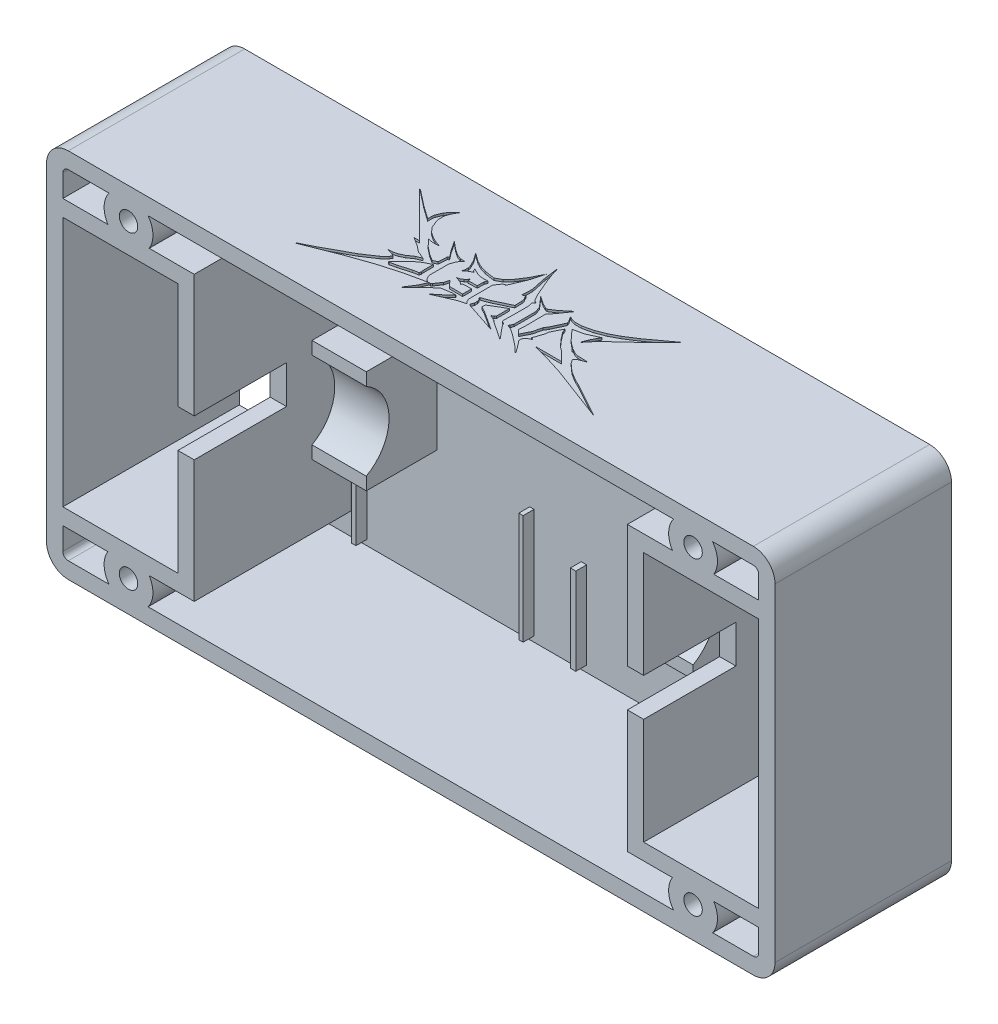
SolidWorks part; units mm, degrees
material "Overture Super PLA Plus"
ref_plane "Front Plane" through (0, 0, 0) normal (0, 0, 1) x (1, 0, 0)
ref_plane "Top Plane" through (0, 0, 0) normal (0, 1, 0) x (1, 0, 0)
ref_plane "Right Plane" through (0, 0, 0) normal (1, 0, 0) x (0, 0, -1)
sketch "Base_Footprint" plane through (0, 0, 0) normal (0, 0, 1) x (1, 0, 0)
  line L1 (-67.1, -34.2) -> (67.1, -34.2)
  line L2 (-67.1, -34.2) -> (-67.1, 34.2)
  line L3 (-67.1, 34.2) -> (67.1, 34.2)
  line L4 (67.1, -34.2) -> (67.1, 34.2)
  dimension "R1_Width" = 134.2
  dimension "R1_Length" = 68.4
  dimension "R1_X" = 67.1
  dimension "R1_Y" = 34.2
extrude "Unbroken_Floor" add sketch "Base_Footprint" along normal blind 2.6
sketch "Shell_Profile" plane through (0, 0, 0) normal (0, 0, 1) x (1, 0, 0)
  line L1 (-67.1, -34.2) -> (67.1, -34.2)
  line L2 (-67.1, -34.2) -> (-67.1, 34.2)
  line L3 (-67.1, 34.2) -> (67.1, 34.2)
  line L4 (67.1, -34.2) -> (67.1, 34.2)
  line L6 (-64.1, -31.2) -> (64.1, -31.2)
  line L7 (-64.1, -31.2) -> (-64.1, 31.2)
  line L8 (-64.1, 31.2) -> (64.1, 31.2)
  line L9 (64.1, -31.2) -> (64.1, 31.2)
  dimension "R1_Width" = 134.2
  dimension "R1_Length" = 68.4
  dimension "R1_X" = 67.1
  dimension "R1_Y" = 34.2
  dimension "R2_Width" = 128.2
  dimension "R2_Length" = 62.4
  dimension "R2_X" = 64.1
  dimension "R2_Y" = 31.2
extrude "Three_mm_Perimeter" add sketch "Shell_Profile" along normal blind 32.5
sketch "Wheel_Well_Profile" plane through (0, 0, 0) normal (0, 0, 1) x (1, 0, 0)
  line L1 (42.9, -23.1) -> (64.1, -23.1)
  line L2 (42.9, -23.1) -> (42.9, 23.1)
  line L3 (42.9, 23.1) -> (64.1, 23.1)
  line L4 (64.1, -23.1) -> (64.1, 23.1)
  line L6 (-64.1, -23.1) -> (-42.9, -23.1)
  line L7 (-64.1, -23.1) -> (-64.1, 23.1)
  line L8 (-64.1, 23.1) -> (-42.9, 23.1)
  line L9 (-42.9, -23.1) -> (-42.9, 23.1)
  dimension "R2_X" = 64.1
  dimension "R1_Width" = 21.2
  dimension "R1_Length" = 46.2
  dimension "R1_X" = 42.9
  dimension "R1_Y" = 23.1
  dimension "R2_Width" = 21.2
  dimension "R2_Length" = 46.2
  dimension "R2_Y" = 23.1
extrude "Open_Wheel_Wells" cut sketch "Wheel_Well_Profile" against normal blind 38 from offset 36
sketch "Wheel_Guard_Profile" plane through (0, 0, 0) normal (0, 0, 1) x (1, 0, 0)
  line L1 (39.9, -23.1) -> (42.9, -23.1)
  line L2 (39.9, -23.1) -> (39.9, 23.1)
  line L3 (39.9, 23.1) -> (42.9, 23.1)
  line L4 (42.9, -23.1) -> (42.9, 23.1)
  line L6 (-42.9, -23.1) -> (-39.9, -23.1)
  line L7 (-42.9, -23.1) -> (-42.9, 23.1)
  line L8 (-42.9, 23.1) -> (-39.9, 23.1)
  line L9 (-39.9, -23.1) -> (-39.9, 23.1)
  dimension "R1_Width" = 3
  dimension "R1_Length" = 46.2
  dimension "R1_X" = 39.9
  dimension "R1_Y" = 23.1
  dimension "R2_Width" = 3
  dimension "R2_Length" = 46.2
  dimension "R2_X" = 42.9
  dimension "R2_Y" = 23.1
extrude "Inner_Wheel_Guards" add sketch "Wheel_Guard_Profile" along normal blind 32.5
sketch "Wheel_Return_Profile" plane through (0, 0, 0) normal (0, 0, 1) x (1, 0, 0)
  line L1 (-64.1, -26.1) -> (-39.9, -26.1)
  line L2 (-64.1, -26.1) -> (-64.1, -23.1)
  line L3 (-64.1, -23.1) -> (-39.9, -23.1)
  line L4 (-39.9, -26.1) -> (-39.9, -23.1)
  line L6 (-64.1, 23.1) -> (-39.9, 23.1)
  line L7 (-64.1, 23.1) -> (-64.1, 26.1)
  line L8 (-64.1, 26.1) -> (-39.9, 26.1)
  line L9 (-39.9, 23.1) -> (-39.9, 26.1)
  line L11 (39.9, -26.1) -> (64.1, -26.1)
  line L12 (39.9, -26.1) -> (39.9, -23.1)
  line L13 (39.9, -23.1) -> (64.1, -23.1)
  line L14 (64.1, -26.1) -> (64.1, -23.1)
  line L16 (39.9, 23.1) -> (64.1, 23.1)
  line L17 (39.9, 23.1) -> (39.9, 26.1)
  line L18 (39.9, 26.1) -> (64.1, 26.1)
  line L19 (64.1, 23.1) -> (64.1, 26.1)
  dimension "R1_Width" = 24.2
  dimension "R1_Length" = 3
  dimension "R1_X" = 64.1
  dimension "R1_Y" = 26.1
  dimension "R2_Width" = 24.2
  dimension "R2_Length" = 3
  dimension "R2_X" = 64.1
  dimension "R2_Y" = 23.1
  dimension "R3_Width" = 24.2
  dimension "R3_Length" = 3
  dimension "R3_X" = 39.9
  dimension "R3_Y" = 26.1
  dimension "R4_Width" = 24.2
  dimension "R4_Length" = 3
  dimension "R4_X" = 39.9
  dimension "R4_Y" = 23.1
extrude "Wheel_Return_Ribs" add sketch "Wheel_Return_Profile" along normal blind 32.5
sketch "Shaft_Drop_In_Profile" plane through (0, 0, 0) normal (0, 0, 1) x (1, 0, 0)
  line L1 (-43.2, -3.5) -> (-39.5, -3.5)
  line L2 (-43.2, -3.5) -> (-43.2, 3.5)
  line L3 (-43.2, 3.5) -> (-39.5, 3.5)
  line L4 (-39.5, -3.5) -> (-39.5, 3.5)
  line L6 (39.5, -3.5) -> (43.2, -3.5)
  line L7 (39.5, -3.5) -> (39.5, 3.5)
  line L8 (39.5, 3.5) -> (43.2, 3.5)
  line L9 (43.2, -3.5) -> (43.2, 3.5)
  dimension "R1_Width" = 3.7
  dimension "R1_Length" = 7
  dimension "R1_X" = 43.2
  dimension "R1_Y" = 3.5
  dimension "R2_Width" = 3.7
  dimension "R2_Length" = 7
  dimension "R2_X" = 39.5
  dimension "R2_Y" = 3.5
extrude "Open_Shaft_Notches" cut sketch "Shaft_Drop_In_Profile" against normal blind 17 from offset 32.5
sketch "Lower_Cradle_Blocks_Profile" plane through (0, 0, 0) normal (0, 0, 1) x (1, 0, 0)
  line L1 (-35.1, -9.5) -> (-25.1, -9.5)
  line L2 (-35.1, -9.5) -> (-35.1, 9.5)
  line L3 (-35.1, 9.5) -> (-25.1, 9.5)
  line L4 (-25.1, -9.5) -> (-25.1, 9.5)
  line L6 (25.1, -9.5) -> (35.1, -9.5)
  line L7 (25.1, -9.5) -> (25.1, 9.5)
  line L8 (25.1, 9.5) -> (35.1, 9.5)
  line L9 (35.1, -9.5) -> (35.1, 9.5)
  dimension "R1_Width" = 10
  dimension "R1_Length" = 19
  dimension "R1_X" = 35.1
  dimension "R1_Y" = 9.5
  dimension "R2_Width" = 10
  dimension "R2_Length" = 19
  dimension "R2_X" = 25.1
  dimension "R2_Y" = 9.5
extrude "Lower_Motor_Cradles" add sketch "Lower_Cradle_Blocks_Profile" along normal blind 15.6
sketch "Lower_Cradle_Radius_Profile" plane through (0, 0, 0) normal (1, 0, 0) x (0, 0, -1)
  circle A0 centre (-19.6, 0) radius 8.2
  dimension "C1_Diameter" = 16.4
  dimension "Motor_Axis_Height" = 19.6
extrude "Lower_Cradle_Seats_R8p2" cut sketch "Lower_Cradle_Radius_Profile" against normal blind 72 from offset 36
sketch "Battery_Side_Guides_Profile" plane through (0, 0, 0) normal (0, 0, 1) x (1, 0, 0)
  line L1 (-31.5, 10) -> (-28.5, 10)
  line L2 (-31.5, 10) -> (-31.5, 31.2)
  line L3 (-31.5, 31.2) -> (-28.5, 31.2)
  line L4 (-28.5, 10) -> (-28.5, 31.2)
  line L6 (28.5, 10) -> (31.5, 10)
  line L7 (28.5, 10) -> (28.5, 31.2)
  line L8 (28.5, 31.2) -> (31.5, 31.2)
  line L9 (31.5, 10) -> (31.5, 31.2)
  dimension "R1_Width" = 3
  dimension "R1_Length" = 21.2
  dimension "R1_X" = 31.5
  dimension "R1_Y" = 10
  dimension "R2_Width" = 3
  dimension "R2_Length" = 21.2
  dimension "R2_X" = 28.5
  dimension "R2_Y" = 10
extrude "Battery_Side_Guides" add sketch "Battery_Side_Guides_Profile" along normal blind 5.6
sketch "Electronics_Locators_Profile" plane through (0, 0, 0) normal (0, 0, 1) x (1, 0, 0)
  line L1 (-38.8, -30.2) -> (-38, -30.2)
  line L2 (-38.8, -30.2) -> (-38.8, -10)
  line L3 (-38.8, -10) -> (-38, -10)
  line L4 (-38, -30.2) -> (-38, -10)
  line L6 (-8, -30.2) -> (-7.2, -30.2)
  line L7 (-8, -30.2) -> (-8, -10)
  line L8 (-8, -10) -> (-7.2, -10)
  line L9 (-7.2, -30.2) -> (-7.2, -10)
  line L11 (1.5, -30) -> (2.5, -30)
  line L12 (1.5, -30) -> (1.5, -14)
  line L13 (1.5, -14) -> (2.5, -14)
  line L14 (2.5, -30) -> (2.5, -14)
  line L16 (33.5, -30) -> (34.5, -30)
  line L17 (33.5, -30) -> (33.5, -14)
  line L18 (33.5, -14) -> (34.5, -14)
  line L19 (34.5, -30) -> (34.5, -14)
  dimension "R1_Width" = 0.8
  dimension "R1_Length" = 20.2
  dimension "R1_X" = 38.8
  dimension "R1_Y" = 30.2
  dimension "R2_Width" = 0.8
  dimension "R2_Length" = 20.2
  dimension "R2_X" = 8
  dimension "R2_Y" = 30.2
  dimension "R3_Width" = 1
  dimension "R3_Length" = 16
  dimension "R3_X" = 1.5
  dimension "R3_Y" = 30
  dimension "R4_Width" = 1
  dimension "R4_Length" = 16
  dimension "R4_X" = 33.5
  dimension "R4_Y" = 30
extrude "Electronics_Locators" add sketch "Electronics_Locators_Profile" along normal blind 4.6
sketch "Lid_Screw_Boss_Profile" plane through (0, 0, 0) normal (0, 0, 1) x (1, 0, 0)
  circle A0 centre (-52, -28.5) radius 4.5
  circle A1 centre (-52, 28.5) radius 4.5
  circle A2 centre (52, -28.5) radius 4.5
  circle A3 centre (52, 28.5) radius 4.5
  dimension "C1_Diameter" = 9
  dimension "C2_Diameter" = 9
  dimension "C3_Diameter" = 9
  dimension "C4_Diameter" = 9
extrude "Reinforced_M3_Bosses" add sketch "Lid_Screw_Boss_Profile" along normal blind 32.5
sketch "M3_Through_Holes_Profile" plane through (0, 0, 0) normal (0, 0, 1) x (1, 0, 0)
  circle A0 centre (-52, -28.5) radius 1.7
  circle A1 centre (-52, 28.5) radius 1.7
  circle A2 centre (52, -28.5) radius 1.7
  circle A3 centre (52, 28.5) radius 1.7
  dimension "C1_Diameter" = 3.4
  dimension "C2_Diameter" = 3.4
  dimension "C3_Diameter" = 3.4
  dimension "C4_Diameter" = 3.4
extrude "M3_Through_Holes" cut sketch "M3_Through_Holes_Profile" against normal blind 36 from offset 35.5
sketch "Captive_Nut_Pockets_Profile" plane through (0, 0, 0) normal (0, 0, 1) x (1, 0, 0)
  line L0 (-48.7091, -28.5) -> (-50.3546, -25.65)
  line L1 (-50.3546, -25.65) -> (-53.6454, -25.65)
  line L2 (-53.6454, -25.65) -> (-55.2909, -28.5)
  line L3 (-55.2909, -28.5) -> (-53.6454, -31.35)
  line L4 (-53.6454, -31.35) -> (-50.3546, -31.35)
  line L5 (-50.3546, -31.35) -> (-48.7091, -28.5)
  line L6 (-48.7091, 28.5) -> (-50.3546, 31.35)
  line L7 (-50.3546, 31.35) -> (-53.6454, 31.35)
  line L8 (-53.6454, 31.35) -> (-55.2909, 28.5)
  line L9 (-55.2909, 28.5) -> (-53.6454, 25.65)
  line L10 (-53.6454, 25.65) -> (-50.3546, 25.65)
  line L11 (-50.3546, 25.65) -> (-48.7091, 28.5)
  line L12 (55.2909, -28.5) -> (53.6454, -25.65)
  line L13 (53.6454, -25.65) -> (50.3546, -25.65)
  line L14 (50.3546, -25.65) -> (48.7091, -28.5)
  line L15 (48.7091, -28.5) -> (50.3546, -31.35)
  line L16 (50.3546, -31.35) -> (53.6454, -31.35)
  line L17 (53.6454, -31.35) -> (55.2909, -28.5)
  line L18 (55.2909, 28.5) -> (53.6454, 31.35)
  line L19 (53.6454, 31.35) -> (50.3546, 31.35)
  line L20 (50.3546, 31.35) -> (48.7091, 28.5)
  line L21 (48.7091, 28.5) -> (50.3546, 25.65)
  line L22 (50.3546, 25.65) -> (53.6454, 25.65)
  line L23 (53.6454, 25.65) -> (55.2909, 28.5)
extrude "M3_Hex_Nut_Pockets_Underside" cut sketch "Captive_Nut_Pockets_Profile" against normal blind 2.7 from offset 2.6
fillet "Outer_Corners_R4" radius 4 4 edges at (-67.1, 34.2, 16.25) (67.1, 34.2, 16.25) (67.1, -34.2, 16.25) (-67.1, -34.2, 16.25)
fillet "Inner_Corners_R1" radius 1 4 edges at (-64.1, -31.2, 17.55) (64.1, -31.2, 17.55) (64.1, 31.2, 17.55) (-64.1, 31.2, 17.55)
fillet "Wheel_Return_Root_Fillets_R1" radius 1 10 edges at (-44.0467, -26.1, 2.6) (-59.9533, -26.1, 2.6) (44.0467, 26.1, 2.6) (59.9533, 26.1, 2.6) (59.9533, -26.1, 2.6) (44.0467, -26.1, 2.6) (-44.0467, 26.1, 2.6) (-59.9533, 26.1, 2.6) (-39.9, 0, 2.6) (39.9, 0, 2.6)
sketch "VIPER_Wordmark_Native_Profile" plane through (0, 0, 0) normal (0, 1, 0) x (1, 0, 0)
  line L0 (27.5, -26.3235) -> (17.4068, -22.5385)
  line L1 (17.4068, -22.5385) -> (13.8978, -21.4346)
  line L2 (13.8978, -21.4346) -> (11.3351, -20.7643)
  line L3 (11.3351, -20.7643) -> (11.2957, -20.6855)
  line L4 (11.2957, -20.6855) -> (15.948, -20.6855)
  line L5 (15.948, -20.6855) -> (14.2133, -18.9507)
  line L6 (14.2133, -18.9507) -> (13.543, -18.4776)
  line L7 (13.543, -18.4776) -> (12.3208, -17.1371)
  line L8 (12.3208, -17.1371) -> (11.3746, -15.8754)
  line L9 (11.3746, -15.8754) -> (11.0986, -15.1658)
  line L10 (11.0986, -15.1658) -> (10.0735, -17.2159)
  line L11 (10.0735, -17.2159) -> (10.0735, -17.6496)
  line L12 (10.0735, -17.6496) -> (9.5609, -19.2267)
  line L13 (9.5609, -19.2267) -> (9.3638, -19.5815)
  line L14 (9.3638, -19.5815) -> (9.7975, -19.8181)
  line L15 (9.7975, -19.8181) -> (9.7975, -19.897)
  line L16 (9.7975, -19.897) -> (9.5215, -19.9364)
  line L17 (9.5215, -19.9364) -> (9.0878, -20.2124)
  line L18 (9.0878, -20.2124) -> (8.7724, -20.5278)
  line L19 (8.7724, -20.5278) -> (8.6147, -20.8432)
  line L20 (8.6147, -20.8432) -> (8.6541, -21.2375)
  line L21 (8.6541, -21.2375) -> (9.7581, -22.6568)
  line L22 (9.7581, -22.6568) -> (10.31, -23.4453)
  line L23 (10.31, -23.4453) -> (10.2706, -23.5242)
  line L24 (10.2706, -23.5242) -> (9.1272, -22.4597)
  line L25 (9.1272, -22.4597) -> (7.1559, -20.922)
  line L26 (7.1559, -20.922) -> (5.9731, -20.1335)
  line L27 (5.9731, -20.1335) -> (5.224, -19.8575)
  line L28 (5.224, -19.8575) -> (5.4211, -19.621)
  line L29 (5.4211, -19.621) -> (5.6183, -19.069)
  line L30 (5.6183, -19.069) -> (5.6183, -15.2446)
  line L31 (5.6183, -15.2446) -> (5.5394, -14.8504)
  line L32 (5.5394, -14.8504) -> (5.224, -14.0224)
  line L33 (5.224, -14.0224) -> (3.6864, -12.2482)
  line L34 (3.6864, -12.2482) -> (5.0269, -13.155)
  line L35 (5.0269, -13.155) -> (5.9731, -13.6281)
  line L36 (5.9731, -13.6281) -> (6.2491, -13.6676)
  line L37 (6.2491, -13.6676) -> (7.4713, -12.879)
  line L38 (7.4713, -12.879) -> (9.3244, -11.3414)
  line L39 (9.3244, -11.3414) -> (7.6685, -13.707)
  line L40 (7.6685, -13.707) -> (6.9194, -14.5744)
  line L41 (6.9194, -14.5744) -> (6.9588, -18.1228)
  line L42 (6.9588, -18.1228) -> (6.8799, -19.5815)
  line L43 (6.8799, -19.5815) -> (7.629, -20.2518)
  line L44 (7.629, -20.2518) -> (8.457, -18.5959)
  line L45 (8.457, -18.5959) -> (8.8513, -17.0188)
  line L46 (8.8513, -17.0188) -> (9.2849, -16.3091)
  line L47 (9.2849, -16.3091) -> (10.3495, -14.0224)
  line L48 (10.3495, -14.0224) -> (10.1918, -13.5887)
  line L49 (10.1918, -13.5887) -> (9.6398, -12.7213)
  line L50 (9.6398, -12.7213) -> (10.2312, -12.9973)
  line L51 (10.2312, -12.9973) -> (10.9014, -13.155)
  line L52 (10.9014, -13.155) -> (12.1237, -13.155)
  line L53 (12.1237, -13.155) -> (13.9767, -12.7213)
  line L54 (13.9767, -12.7213) -> (15.7115, -12.0511)
  line L55 (15.7115, -12.0511) -> (17.3674, -11.1837)
  line L56 (17.3674, -11.1837) -> (19.5358, -9.8038)
  line L57 (19.5358, -9.8038) -> (24.267, -6.3342)
  line L58 (24.267, -6.3342) -> (20.0484, -10.474)
  line L59 (20.0484, -10.474) -> (17.4068, -12.9185)
  line L60 (17.4068, -12.9185) -> (15.5932, -14.7321)
  line L61 (15.5932, -14.7321) -> (14.6864, -15.836)
  line L62 (14.6864, -15.836) -> (14.647, -15.7177)
  line L63 (14.647, -15.7177) -> (15.0806, -14.6138)
  line L64 (15.0806, -14.6138) -> (15.8692, -13.155)
  line L65 (15.8692, -13.155) -> (13.6219, -14.1801)
  line L66 (13.6219, -14.1801) -> (11.7688, -14.5744)
  line L67 (11.7688, -14.5744) -> (13.5036, -16.4668)
  line L68 (13.5036, -16.4668) -> (14.4104, -17.2159)
  line L69 (14.4104, -17.2159) -> (14.7258, -17.3737)
  line L70 (14.7258, -17.3737) -> (15.0018, -17.7679)
  line L71 (15.0018, -17.7679) -> (15.1201, -17.6891)
  line L72 (15.1201, -17.6891) -> (15.9086, -18.1228)
  line L73 (15.9086, -18.1228) -> (16.5, -18.2805)
  line L74 (16.5, -18.2805) -> (18.4713, -18.3593)
  line L75 (18.4713, -18.3593) -> (17.2097, -18.8719)
  line L76 (17.2097, -18.8719) -> (16.8154, -19.1478)
  line L77 (16.8154, -19.1478) -> (16.6577, -19.3844)
  line L78 (16.6577, -19.3844) -> (17.1308, -20.0941)
  line L79 (17.1308, -20.0941) -> (18.5502, -21.3557)
  line L80 (18.5502, -21.3557) -> (20.0878, -22.302)
  line L81 (20.0878, -22.302) -> (21.31, -22.8934)
  line L82 (21.31, -22.8934) -> (27.5, -26.3235)
  line L83 (-27.4211, -26.2841) -> (-27.5, -26.2841)
  line L84 (-27.5, -26.2841) -> (-27.4606, -26.2052)
  line L85 (-27.4606, -26.2052) -> (-25.0161, -24.983)
  line L86 (-25.0161, -24.983) -> (-19.9695, -22.2231)
  line L87 (-19.9695, -22.2231) -> (-17.6039, -20.6461)
  line L88 (-17.6039, -20.6461) -> (-16.6971, -19.7787)
  line L89 (-16.6971, -19.7787) -> (-16.4211, -19.345)
  line L90 (-16.4211, -19.345) -> (-16.8943, -19.1084)
  line L91 (-16.8943, -19.1084) -> (-18.0771, -18.793)
  line L92 (-18.0771, -18.793) -> (-17.1308, -18.7536)
  line L93 (-17.1308, -18.7536) -> (-16.3029, -18.5565)
  line L94 (-16.3029, -18.5565) -> (-15.3961, -18.1228)
  line L95 (-15.3961, -18.1228) -> (-14.2527, -17.3342)
  line L96 (-14.2527, -17.3342) -> (-13.3065, -16.9794)
  line L97 (-13.3065, -16.9794) -> (-14.3315, -16.5063)
  line L98 (-14.3315, -16.5063) -> (-14.6075, -16.4668)
  line L99 (-14.6075, -16.4668) -> (-15.7903, -15.5206)
  line L100 (-15.7903, -15.5206) -> (-17.4068, -14.4955)
  line L101 (-17.4068, -14.4955) -> (-16.4211, -14.4955)
  line L102 (-16.4211, -14.4955) -> (-24.6219, -6.2554)
  line L103 (-24.6219, -6.2554) -> (-24.6219, -6.1765)
  line L104 (-24.6219, -6.1765) -> (-24.4642, -6.2554)
  line L105 (-24.4642, -6.2554) -> (-21.5466, -8.5421)
  line L106 (-21.5466, -8.5421) -> (-19.1416, -10.2375)
  line L107 (-19.1416, -10.2375) -> (-19.181, -9.4095)
  line L108 (-19.181, -9.4095) -> (-19.1022, -8.9758)
  line L109 (-19.1022, -8.9758) -> (-18.629, -7.8719)
  line L110 (-18.629, -7.8719) -> (-18.1165, -7.1622)
  line L111 (-18.1165, -7.1622) -> (-17.0914, -6.1765)
  line L112 (-17.0914, -6.1765) -> (-17.7616, -7.3593)
  line L113 (-17.7616, -7.3593) -> (-18.0376, -8.1873)
  line L114 (-18.0376, -8.1873) -> (-18.0771, -9.2518)
  line L115 (-18.0771, -9.2518) -> (-17.9588, -9.8038)
  line L116 (-17.9588, -9.8038) -> (-17.3674, -11.2231)
  line L117 (-17.3674, -11.2231) -> (-16.6183, -12.0511)
  line L118 (-16.6183, -12.0511) -> (-15.7115, -12.6819)
  line L119 (-15.7115, -12.6819) -> (-14.8441, -13.1156)
  line L120 (-14.8441, -13.1156) -> (-13.7007, -13.5099)
  line L121 (-13.7007, -13.5099) -> (-14.9229, -13.5493)
  line L122 (-14.9229, -13.5493) -> (-15.8297, -13.3916)
  line L123 (-15.8297, -13.3916) -> (-14.6864, -14.6138)
  line L124 (-14.6864, -14.6138) -> (-13.3065, -15.7177)
  line L125 (-13.3065, -15.7177) -> (-12.0842, -16.4668)
  line L126 (-12.0842, -16.4668) -> (-11.3351, -16.112)
  line L127 (-11.3351, -16.112) -> (-11.2563, -14.6138)
  line L128 (-11.2563, -14.6138) -> (-11.2168, -14.4561)
  line L129 (-11.2168, -14.4561) -> (-10.9409, -14.4167)
  line L130 (-10.9409, -14.4167) -> (-11.8082, -13.3127)
  line L131 (-11.8082, -13.3127) -> (-13.1093, -11.3808)
  line L132 (-13.1093, -11.3808) -> (-11.7688, -12.4848)
  line L133 (-11.7688, -12.4848) -> (-10.6649, -13.2339)
  line L134 (-10.6649, -13.2339) -> (-9.7975, -13.5887)
  line L135 (-9.7975, -13.5887) -> (-8.8513, -13.6281)
  line L136 (-8.8513, -13.6281) -> (-9.3638, -14.1013)
  line L137 (-9.3638, -14.1013) -> (-9.6398, -14.4955)
  line L138 (-9.6398, -14.4955) -> (-9.9946, -15.5206)
  line L139 (-9.9946, -15.5206) -> (-9.9946, -19.1478)
  line L140 (-9.9946, -19.1478) -> (-9.6398, -19.897)
  line L141 (-9.6398, -19.897) -> (-9.0484, -20.3306)
  line L142 (-9.0484, -20.3306) -> (-12.8728, -21.1586)
  line L143 (-12.8728, -21.1586) -> (-16.8548, -22.302)
  line L144 (-16.8548, -22.302) -> (-21.2312, -23.8396)
  line L145 (-21.2312, -23.8396) -> (-27.4211, -26.2841)
  line L146 (-10.586, -23.5636) -> (-10.6254, -23.4848)
  line L147 (-10.6254, -23.4848) -> (-9.4427, -21.6317)
  line L148 (-9.4427, -21.6317) -> (-8.8513, -20.2912)
  line L149 (-8.8513, -20.2912) -> (-8.5753, -20.2912)
  line L150 (-8.5753, -20.2912) -> (-8.3781, -20.1335)
  line L151 (-8.3781, -20.1335) -> (-7.5502, -18.9113)
  line L152 (-7.5502, -18.9113) -> (-7.2742, -18.0045)
  line L153 (-7.2742, -18.0045) -> (-6.3674, -19.0296)
  line L154 (-6.3674, -19.0296) -> (-3.9229, -19.0296)
  line L155 (-3.9229, -19.0296) -> (-3.9229, -17.3737)
  line L156 (-3.9229, -17.3737) -> (-5.5789, -17.4131)
  line L157 (-5.5789, -17.4131) -> (-5.6183, -17.7679)
  line L158 (-5.6183, -17.7679) -> (-5.776, -17.5314)
  line L159 (-5.776, -17.5314) -> (-6.1308, -17.2948)
  line L160 (-6.1308, -17.2948) -> (-7.1559, -16.9794)
  line L161 (-7.1559, -16.9794) -> (-6.6039, -16.8217)
  line L162 (-6.6039, -16.8217) -> (-6.1308, -16.5457)
  line L163 (-6.1308, -16.5457) -> (-5.6183, -15.9937)
  line L164 (-5.6183, -15.9937) -> (-5.5394, -16.388)
  line L165 (-5.5394, -16.388) -> (-3.9229, -16.3486)
  line L166 (-3.9229, -16.3486) -> (-3.8835, -15.0869)
  line L167 (-3.8835, -15.0869) -> (-3.6864, -14.6138)
  line L168 (-3.6864, -14.6138) -> (-4.6326, -14.6532)
  line L169 (-4.6326, -14.6532) -> (-5.5, -14.5349)
  line L170 (-5.5, -14.5349) -> (-6.8011, -13.9041)
  line L171 (-6.8011, -13.9041) -> (-6.6039, -14.3772)
  line L172 (-6.6039, -14.3772) -> (-6.3674, -14.4561)
  line L173 (-6.3674, -14.4561) -> (-6.3674, -14.5349)
  line L174 (-6.3674, -14.5349) -> (-6.9588, -14.8109)
  line L175 (-6.9588, -14.8109) -> (-7.7079, -15.4023)
  line L176 (-7.7079, -15.4023) -> (-7.5896, -14.9686)
  line L177 (-7.5896, -14.9686) -> (-7.5896, -14.2984)
  line L178 (-7.5896, -14.2984) -> (-7.7867, -13.6281)
  line L179 (-7.7867, -13.6281) -> (-8.3387, -12.5636)
  line L180 (-8.3387, -12.5636) -> (-9.2455, -11.302)
  line L181 (-9.2455, -11.302) -> (-7.7079, -12.4059)
  line L182 (-7.7079, -12.4059) -> (-6.6828, -12.9185)
  line L183 (-6.6828, -12.9185) -> (-5.4606, -13.3127)
  line L184 (-5.4606, -13.3127) -> (-3.6075, -13.5887)
  line L185 (-3.6075, -13.5887) -> (-2.543, -12.9973)
  line L186 (-2.543, -12.9973) -> (-1.5573, -11.9722)
  line L187 (-1.5573, -11.9722) -> (-0.414, -10.2375)
  line L188 (-0.414, -10.2375) -> (0.6505, -8.069)
  line L189 (0.6505, -8.069) -> (-0.0986, -10.7106)
  line L190 (-0.0986, -10.7106) -> (-1.3602, -13.707)
  line L191 (-1.3602, -13.707) -> (-1.5179, -13.5887)
  line L192 (-1.5179, -13.5887) -> (-1.7545, -13.707)
  line L193 (-1.7545, -13.707) -> (-2.1093, -14.1013)
  line L194 (-2.1093, -14.1013) -> (-2.5824, -14.8898)
  line L195 (-2.5824, -14.8898) -> (-2.5824, -19.2267)
  line L196 (-2.5824, -19.2267) -> (-2.3459, -19.7787)
  line L197 (-2.3459, -19.7787) -> (-1.9516, -20.1729)
  line L198 (-1.9516, -20.1729) -> (-3.4104, -20.5672)
  line L199 (-3.4104, -20.5672) -> (-7.1953, -22.2231)
  line L200 (-7.1953, -22.2231) -> (-5.9731, -21.2769)
  line L201 (-5.9731, -21.2769) -> (-4.3961, -19.8575)
  line L202 (-4.3961, -19.8575) -> (-4.3961, -19.7787)
  line L203 (-4.3961, -19.7787) -> (-5.1452, -19.8181)
  line L204 (-5.1452, -19.8181) -> (-6.8799, -20.0941)
  line L205 (-6.8799, -20.0941) -> (-8.733, -21.6711)
  line L206 (-8.733, -21.6711) -> (-10.586, -23.5636)
  line L207 (6.8405, -22.8934) -> (3.2527, -20.4884)
  line L208 (3.2527, -20.4884) -> (3.1344, -20.3306)
  line L209 (3.1344, -20.3306) -> (2.0699, -19.8575)
  line L210 (2.0699, -19.8575) -> (2.5036, -19.6604)
  line L211 (2.5036, -19.6604) -> (2.7007, -19.4238)
  line L212 (2.7007, -19.4238) -> (2.7007, -17.0188)
  line L213 (2.7007, -17.0188) -> (-0.0591, -18.6747)
  line L214 (-0.0591, -18.6747) -> (-0.0986, -19.3056)
  line L215 (-0.0986, -19.3056) -> (0.8871, -19.8181)
  line L216 (0.8871, -19.8181) -> (4.3566, -22.0654)
  line L217 (4.3566, -22.0654) -> (-1.3996, -20.1729)
  line L218 (-1.3996, -20.1729) -> (-1.6362, -20.0152)
  line L219 (-1.6362, -20.0152) -> (-1.3996, -19.345)
  line L220 (-1.3996, -19.345) -> (-1.3996, -18.793)
  line L221 (-1.3996, -18.793) -> (-1.5573, -18.3593)
  line L222 (-1.5573, -18.3593) -> (-1.7939, -18.0833)
  line L223 (-1.7939, -18.0833) -> (-1.7545, -18.0045)
  line L224 (-1.7545, -18.0045) -> (-0.2957, -17.4525)
  line L225 (-0.2957, -17.4525) -> (2.7007, -16.0332)
  line L226 (2.7007, -16.0332) -> (2.6613, -14.6532)
  line L227 (2.6613, -14.6532) -> (2.5036, -14.0618)
  line L228 (2.5036, -14.0618) -> (2.2276, -13.707)
  line L229 (2.2276, -13.707) -> (2.1882, -13.431)
  line L230 (2.1882, -13.431) -> (1.6756, -13.7464)
  line L231 (1.6756, -13.7464) -> (1.7545, -11.8539)
  line L232 (1.7545, -11.8539) -> (1.1237, -8.897)
  line L233 (1.1237, -8.897) -> (0.8082, -6.4131)
  line L234 (0.8082, -6.4131) -> (0.8871, -6.4525)
  line L235 (0.8871, -6.4525) -> (1.0448, -7.1622)
  line L236 (1.0448, -7.1622) -> (1.7151, -9.0152)
  line L237 (1.7151, -9.0152) -> (3.0556, -12.1299)
  line L238 (3.0556, -12.1299) -> (3.6864, -13.3127)
  line L239 (3.6864, -13.3127) -> (4.0806, -13.6281)
  line L240 (4.0806, -13.6281) -> (4.2778, -13.6676)
  line L241 (4.2778, -13.6676) -> (3.8835, -14.1013)
  line L242 (3.8835, -14.1013) -> (4.0806, -15.0081)
  line L243 (4.0806, -15.0081) -> (4.0412, -19.621)
  line L244 (4.0412, -19.621) -> (4.2384, -19.8181)
  line L245 (4.2384, -19.8181) -> (4.4749, -19.897)
  line L246 (4.4749, -19.897) -> (5.0269, -20.7249)
  line L247 (5.0269, -20.7249) -> (6.8405, -22.8934)
  line L248 (-15.9086, -20.6855) -> (-15.7903, -20.7249)
  line L249 (-15.7903, -20.7249) -> (-14.5681, -20.4489)
  line L250 (-14.5681, -20.4489) -> (-12.3996, -19.8181)
  line L251 (-12.3996, -19.8181) -> (-11.3746, -19.621)
  line L252 (-11.3746, -19.621) -> (-11.2563, -19.3056)
  line L253 (-11.2563, -19.3056) -> (-11.3351, -18.9113)
  line L254 (-11.3351, -18.9113) -> (-11.3351, -17.0188)
  line L255 (-11.3351, -17.0188) -> (-12.6362, -17.6496)
  line L256 (-12.6362, -17.6496) -> (-13.819, -18.517)
  line L257 (-13.819, -18.517) -> (-15.9086, -20.6855)
extrude "VIPER_Rear_Engraved" cut sketch "VIPER_Wordmark_Native_Profile" against normal blind 0.4 from offset 34.2
equation "\"Overall_Width\"= 134.2mm"
equation "\"Overall_Length\"= 68.4mm"
equation "\"Wall\"= 3mm"
equation "\"Floor\"= 2.6mm"
equation "\"Case_Height\"= 32.5mm"
equation "\"Lid_Thickness\"= 3mm"
equation "\"Wheel_Diameter\"= 43.2mm"
equation "\"Wheel_Width\"= 14mm"
equation "\"Wheel_Bay_Inner_X\"= 42.9mm"
equation "\"Wheel_Radial_Clearance\"= 1.5mm"
equation "\"Wheel_Bay_Half_Length\"= \"Wheel_Diameter\"/2+\"Wheel_Radial_Clearance\""
equation "\"Ground_Clearance\"= 2mm"
equation "\"Motor_Axis_Z\"= \"Wheel_Diameter\"/2-\"Ground_Clearance\""
equation "\"Motor_Face_X\"= 38.1mm"
equation "\"Motor_Clamp_Radius\"= 8.2mm"
equation "\"Screw_Clearance\"= 3.4mm"
equation "\"Nut_AF_Clearance\"= 5.7mm"
equation "\"Engraving_Depth\"= 0.4mm"
equation "\"Hub_Offset_Min_Allowed\"= \"Wheel_Bay_Inner_X\"+1mm-\"Motor_Face_X\""
equation "\"Hub_Offset_Max_Allowed\"= \"Overall_Width\"/2-\"Wall\"-1mm-\"Wheel_Width\"-\"Motor_Face_X\""
equation "\"R1_Width@Base_Footprint\" = \"Overall_Width\""
equation "\"R1_Length@Base_Footprint\" = \"Overall_Length\""
equation "\"R1_X@Base_Footprint\" = \"Overall_Width\"/2"
equation "\"R1_Y@Base_Footprint\" = \"Overall_Length\"/2"
equation "\"D1@Unbroken_Floor\" = \"Floor\""
equation "\"R1_Width@Shell_Profile\" = \"Overall_Width\""
equation "\"R1_Length@Shell_Profile\" = \"Overall_Length\""
equation "\"R1_X@Shell_Profile\" = \"Overall_Width\"/2"
equation "\"R1_Y@Shell_Profile\" = \"Overall_Length\"/2"
equation "\"R2_Width@Shell_Profile\" = \"Overall_Width\"-2*\"Wall\""
equation "\"R2_Length@Shell_Profile\" = \"Overall_Length\"-2*\"Wall\""
equation "\"R2_X@Shell_Profile\" = \"Overall_Width\"/2-\"Wall\""
equation "\"R2_Y@Shell_Profile\" = \"Overall_Length\"/2-\"Wall\""
equation "\"D1@Three_mm_Perimeter\" = \"Case_Height\""
equation "\"R1_Width@Wheel_Well_Profile\" = \"Overall_Width\"/2-\"Wall\"-\"Wheel_Bay_Inner_X\""
equation "\"R1_Length@Wheel_Well_Profile\" = 2*\"Wheel_Bay_Half_Length\""
equation "\"R1_X@Wheel_Well_Profile\" = \"Wheel_Bay_Inner_X\""
equation "\"R1_Y@Wheel_Well_Profile\" = \"Wheel_Bay_Half_Length\""
equation "\"R2_Width@Wheel_Well_Profile\" = \"Overall_Width\"/2-\"Wall\"-\"Wheel_Bay_Inner_X\""
equation "\"R2_Length@Wheel_Well_Profile\" = 2*\"Wheel_Bay_Half_Length\""
equation "\"R2_X@Wheel_Well_Profile\" = \"Overall_Width\"/2-\"Wall\""
equation "\"R2_Y@Wheel_Well_Profile\" = \"Wheel_Bay_Half_Length\""
equation "\"D1@Inner_Wheel_Guards\" = \"Case_Height\""
equation "\"D1@Wheel_Return_Ribs\" = \"Case_Height\""
equation "\"C1_Diameter@Lower_Cradle_Radius_Profile\" = 2*\"Motor_Clamp_Radius\""
equation "\"D1@Reinforced_M3_Bosses\" = \"Case_Height\""
equation "\"C1_Diameter@M3_Through_Holes_Profile\" = \"Screw_Clearance\""
equation "\"C2_Diameter@M3_Through_Holes_Profile\" = \"Screw_Clearance\""
equation "\"C3_Diameter@M3_Through_Holes_Profile\" = \"Screw_Clearance\""
equation "\"C4_Diameter@M3_Through_Holes_Profile\" = \"Screw_Clearance\""
equation "\"Motor_Axis_Height@Lower_Cradle_Radius_Profile\" = \"Motor_Axis_Z\""
equation "\"D1@Lower_Motor_Cradles\" = \"Motor_Axis_Z\"-4mm"
equation "\"D1@Open_Shaft_Notches\" = \"Case_Height\"-\"Motor_Axis_Z\"+4.1mm"
equation "\"D1@VIPER_Rear_Engraved\" = \"Engraving_Depth\""
